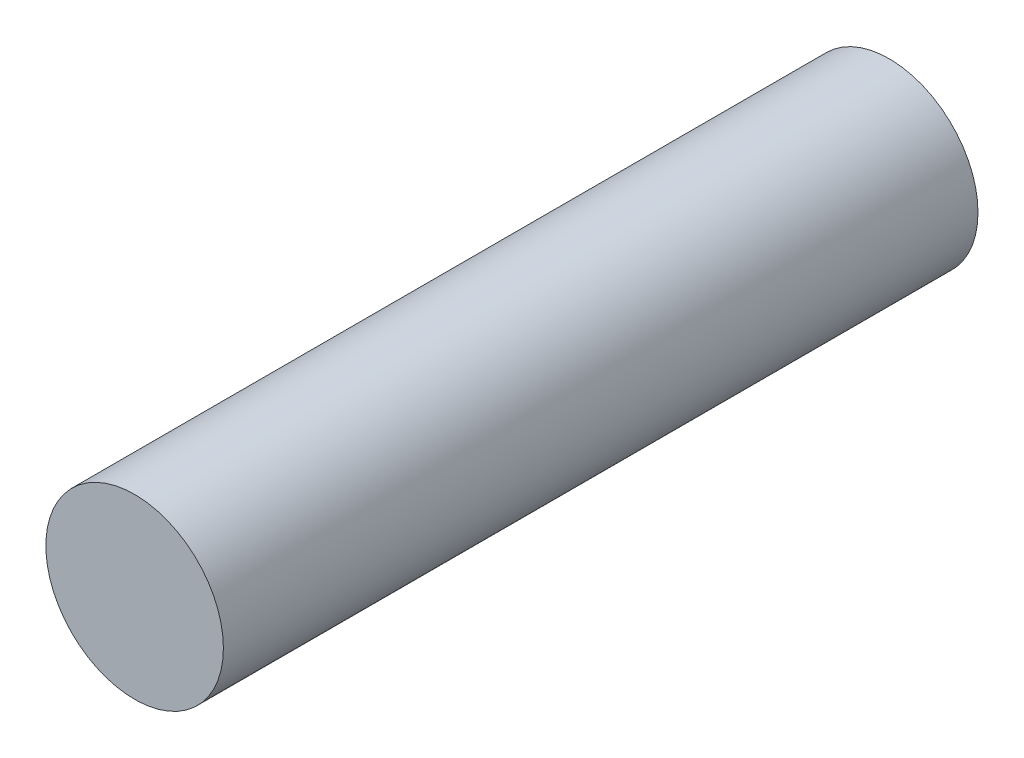
SolidWorks part; units mm, degrees
ref_plane "Спереди" through (0, 0, 0) normal (0, 0, 1) x (1, 0, 0)
ref_plane "Сверху" through (0, 0, 0) normal (0, 1, 0) x (1, 0, 0)
ref_plane "Справа" through (0, 0, 0) normal (1, 0, 0) x (0, 0, -1)
sketch "Эскиз1" plane through (0, 0, 0) normal (0, 0, 1) x (1, 0, 0)
  circle A0 centre (0, 0) radius 1
  dimension "D1" = 2
extrude "Бобышка-Вытянуть1" add sketch "Эскиз1" along normal blind 8.5
